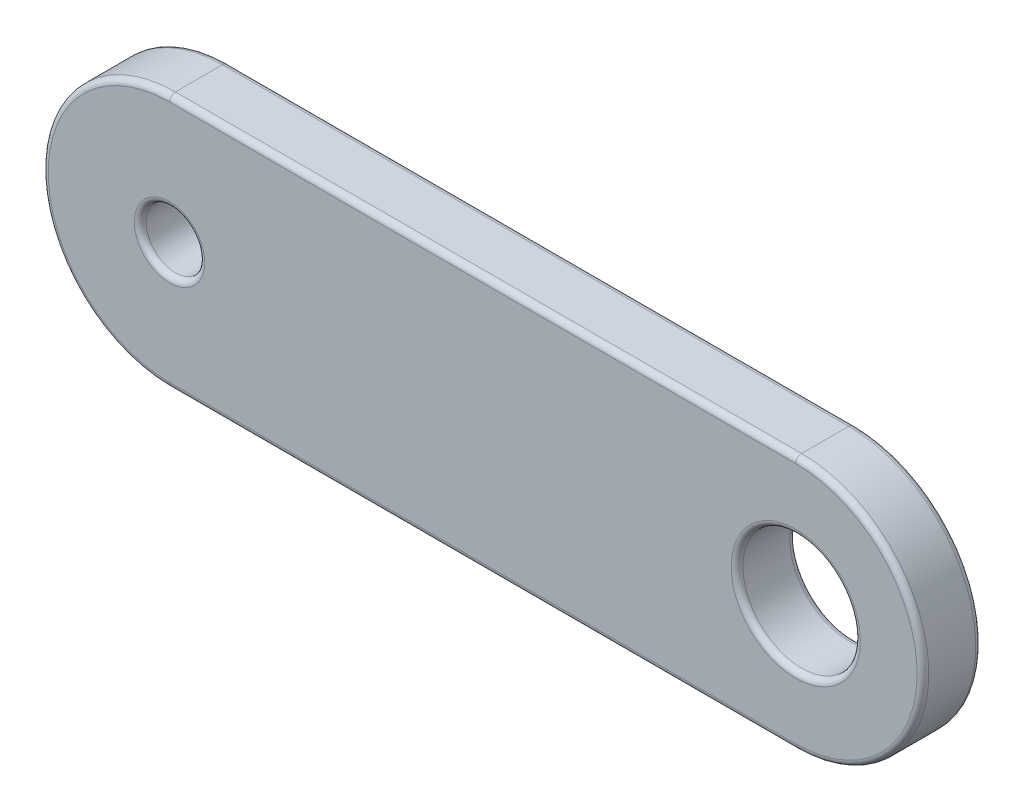
SolidWorks part; units mm, degrees
ref_plane "前视基准面" through (0, 0, 0) normal (0, 0, 1) x (1, 0, 0)
ref_plane "上视基准面" through (0, 0, 0) normal (0, 1, 0) x (1, 0, 0)
ref_plane "右视基准面" through (0, 0, 0) normal (1, 0, 0) x (0, 0, -1)
sketch "草图1" plane through (0, 0, 0) normal (0, 0, 1) x (1, 0, 0)
  line L0 (-8, 0) -> (8, 0) construction
  line L1 (-8, 3.25) -> (8, 3.25)
  line L2 (-8, -3.25) -> (8, -3.25)
  arc A0 (-8, 3.25) -> (-8, -3.25) centre (-8, 0) ccw
  arc A1 (8, -3.25) -> (8, 3.25) centre (8, 0) ccw
  circle A2 centre (-8, 0) radius 0.75
  circle A3 centre (8, 0) radius 1.5
  point P2 (0, 0)
  dimension "D3" = 1.5
  dimension "D4" = 3
  dimension "D1" = 16
  dimension "D2" = 6.5
extrude "凸台-拉伸1" add sketch "草图1" along normal mid plane 1.5
fillet "圆角1" radius 0.15 12 edges at (9.5, 0, -0.75) (-7.25, 0, -0.75) (0, -3.25, -0.75) (11.25, 0, -0.75) (0, 3.25, -0.75) (-11.25, 0, -0.75) (9.5, 0, 0.75) (0, 3.25, 0.75) (11.25, 0, 0.75) (0, -3.25, 0.75) (-11.25, 0, 0.75) (-7.25, 0, 0.75)
